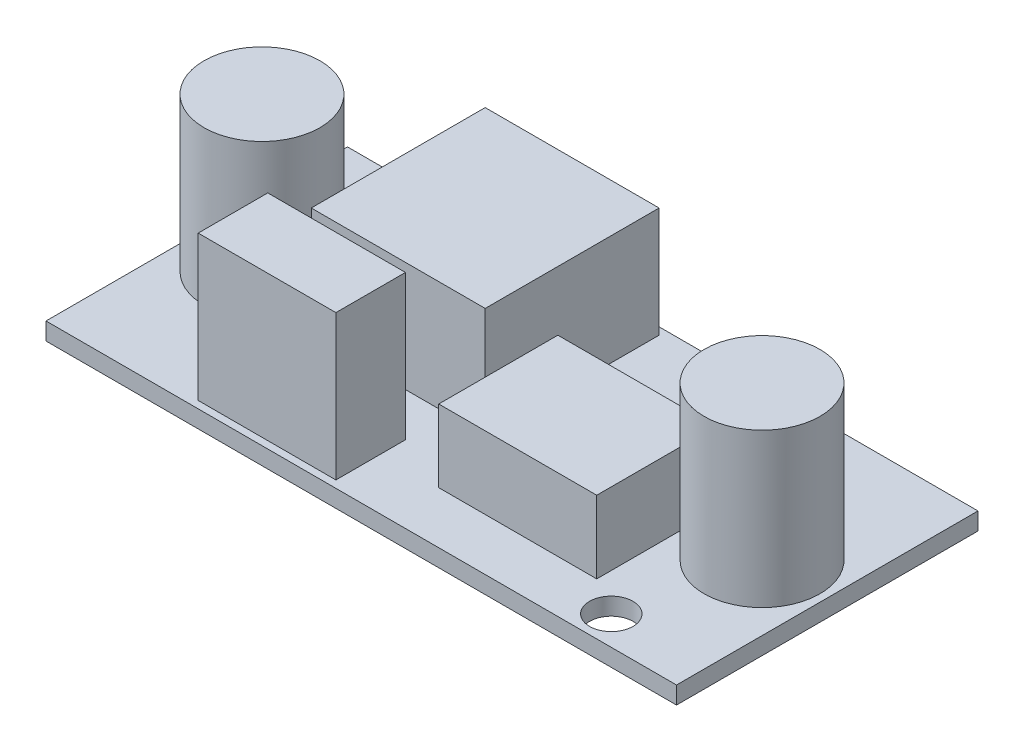
SolidWorks part; units mm, degrees
ref_plane "前视基准面" through (0, 0, 0) normal (0, 0, 1) x (1, 0, 0)
ref_plane "上视基准面" through (0, 0, 0) normal (0, 1, 0) x (1, 0, 0)
ref_plane "右视基准面" through (0, 0, 0) normal (1, 0, 0) x (0, 0, -1)
sketch "草图1" plane through (0, 0, 0) normal (0, 1, 0) x (1, 0, 0)
  line L1 (-21.75, -10.4) -> (21.75, -10.4)
  line L2 (-21.75, -10.4) -> (-21.75, 10.4)
  line L3 (-21.75, 10.4) -> (21.75, 10.4)
  line L4 (21.75, -10.4) -> (21.75, 10.4)
  line L5 (-21.75, -10.4) -> (21.75, 10.4) construction
  line L6 (-21.75, 10.4) -> (21.75, -10.4) construction
  point P0 (0, 0)
  dimension "D1" = 43.5
  dimension "D2" = 20.8
extrude "凸台-拉伸1" add sketch "草图1" along normal blind 1.2
sketch "草图2" plane through (0, 1.2, 0) normal (0, 1, 0) x (1, 0, 0)
  line L0 (-21.75, 10.4) -> (-21.75, -10.4) construction
  line L1 (-11.75, 9.9) -> (0.25, 9.9)
  line L2 (-11.75, 9.9) -> (-11.75, -2.1)
  line L3 (-11.75, -2.1) -> (0.25, -2.1)
  line L4 (0.25, 9.9) -> (0.25, -2.1)
  line L5 (21.75, 10.4) -> (-21.75, 10.4) construction
  dimension "D1" = 12
  dimension "D2" = 10
  dimension "D3" = 0.5
extrude "凸台-拉伸2" add sketch "草图2" along normal blind 7.6
sketch "草图3" plane through (0, 1.2, 0) normal (0, 1, 0) x (1, 0, 0)
  line L0 (-21.75, 0) -> (21.75, 0) construction
  line L1 (-21.75, 10.4) -> (-21.75, -10.4) construction
  line L2 (21.75, -10.4) -> (21.75, 10.4) construction
  circle A0 centre (-17.25, 0) radius 4
  circle A1 centre (17.25, 0) radius 4
  dimension "D1" = 8
  dimension "D3" = 4.5
  dimension "D2" = 4.5
extrude "凸台-拉伸3" add sketch "草图3" along normal blind 10.6
sketch "草图4" plane through (0, 1.2, 0) normal (0, 1, 0) x (1, 0, 0)
  line L0 (-21.75, -10.4) -> (21.75, -10.4) construction
  line L1 (-11.75, -5.1) -> (-2.25, -5.1)
  line L2 (-11.75, -5.1) -> (-11.75, -9.9)
  line L3 (-11.75, -9.9) -> (-2.25, -9.9)
  line L4 (-2.25, -5.1) -> (-2.25, -9.9)
  line L5 (-11.75, 9.9) -> (-11.75, -2.1) construction
  dimension "D1" = 9.5
  dimension "D2" = 4.8
  dimension "D3" = 0.5
extrude "凸台-拉伸4" add sketch "草图4" along normal blind 10
sketch "草图5" plane through (0, 1.2, 0) normal (0, 1, 0) x (1, 0, 0)
  line L1 (1.7583, 1.4066) -> (12.6594, 1.4066)
  line L2 (1.7583, 1.4066) -> (1.7583, -6.8132)
  line L3 (1.7583, -6.8132) -> (12.6594, -6.8132)
  line L4 (12.6594, 1.4066) -> (12.6594, -6.8132)
extrude "凸台-拉伸5" add sketch "草图5" along normal blind 5
sketch "草图6" plane through (0, 1.2, 0) normal (0, 1, 0) x (1, 0, 0)
  line L0 (21.75, -10.4) -> (21.75, 10.4) construction
  line L1 (-21.75, -10.4) -> (21.75, -10.4) construction
  line L2 (21.75, 10.4) -> (-21.75, 10.4) construction
  line L3 (-21.75, 10.4) -> (-21.75, -10.4) construction
  circle A0 centre (15.25, -8.4) radius 1.5
  circle A1 centre (-15.25, 8.4) radius 1.5
  point P8 (15.2089, -9.9341)
  point P9 (15.0724, -9.4895)
  point P14 (-21.75, 8.3078)
  dimension "D1" = 3
  dimension "D2" = 3
  dimension "D3" = 6.5
  dimension "D4" = 2
  dimension "D5" = 2
  dimension "D6" = 6.5
extrude "切除-拉伸1" cut sketch "草图6" against normal blind 5
